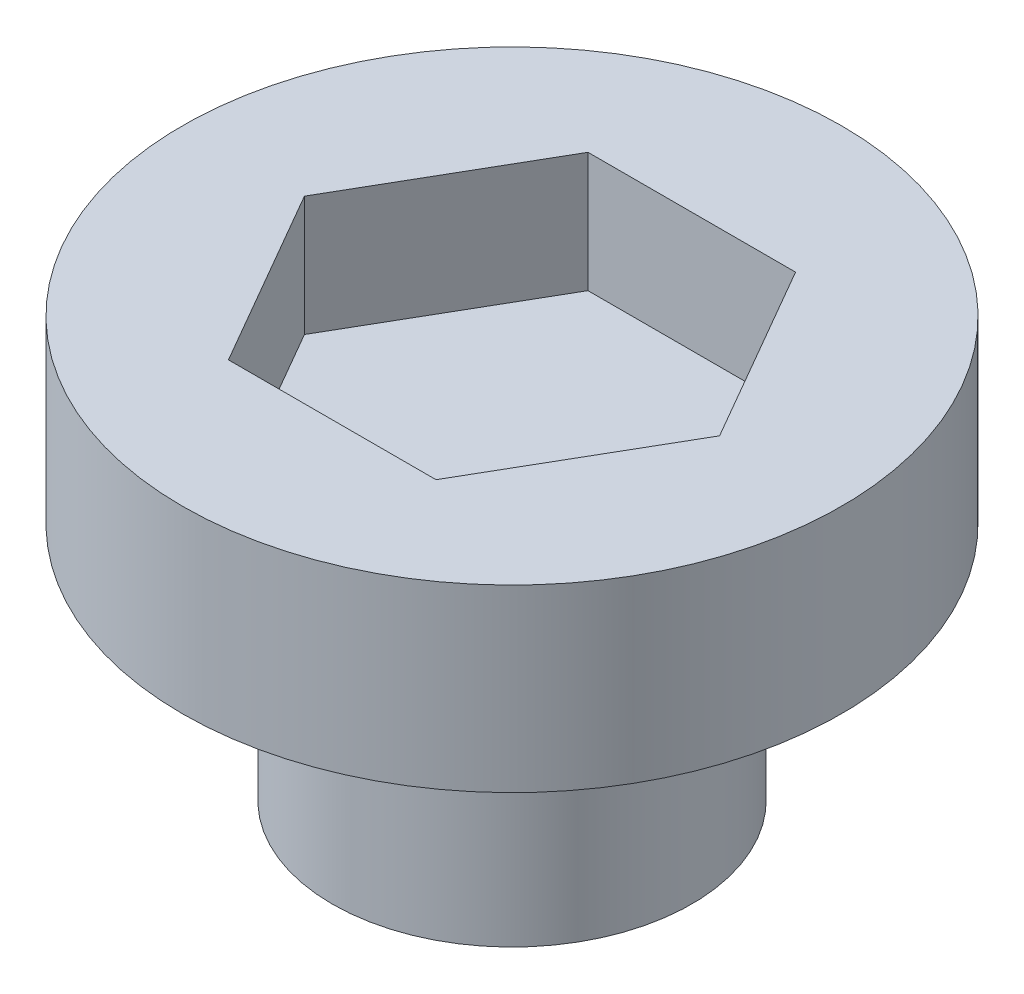
SolidWorks part; units mm, degrees
ref_plane "Спереди" through (0, 0, 0) normal (0, 0, 1) x (1, 0, 0)
ref_plane "Сверху" through (0, 0, 0) normal (0, 1, 0) x (1, 0, 0)
ref_plane "Справа" through (0, 0, 0) normal (1, 0, 0) x (0, 0, -1)
other "Configuration Table"
sketch "Sketch1" plane through (0, 0, 0) normal (0, 0, 1) x (1, 0, 0)
  line L1 (0, 0) -> (1.5, 0)
  line L2 (0, 0) -> (0, 2) construction
  line L3 (0, 2) -> (1.5, 2)
  line L4 (1.5, 0) -> (1.5, 2)
  line L5 (0, 2) -> (2.75, 2)
  line L6 (0, 2) -> (0, 3.5)
  line L7 (0, 3.5) -> (2.75, 3.5)
  line L8 (2.75, 2) -> (2.75, 3.5)
  point P8 (0, 5.7995)
  dimension "D1" = 3
  dimension "D2" = 5.5
  dimension "D3" = 1.5
  dimension "D4" = 2
revolve "Revolve1" add sketch "Sketch1" angle 360 about L2
sketch "Sketch2" plane through (0, 3.5, 0) normal (0, 1, 0) x (1, 0, 0)
  line L1 (-1.7321, 0) -> (-0.866, -1.5)
  line L2 (-0.866, -1.5) -> (0.866, -1.5)
  line L3 (0.866, -1.5) -> (1.7321, 0)
  line L4 (1.7321, 0) -> (0.866, 1.5)
  line L5 (0.866, 1.5) -> (-0.866, 1.5)
  line L6 (-0.866, 1.5) -> (-1.7321, 0)
  circle A0 centre (0, 0) radius 1.5 construction
  dimension "D1" = 3
extrude "Cut-Extrude1" cut sketch "Sketch2" against normal blind 1 contours L6 L1 L2 L3 L4 L5
